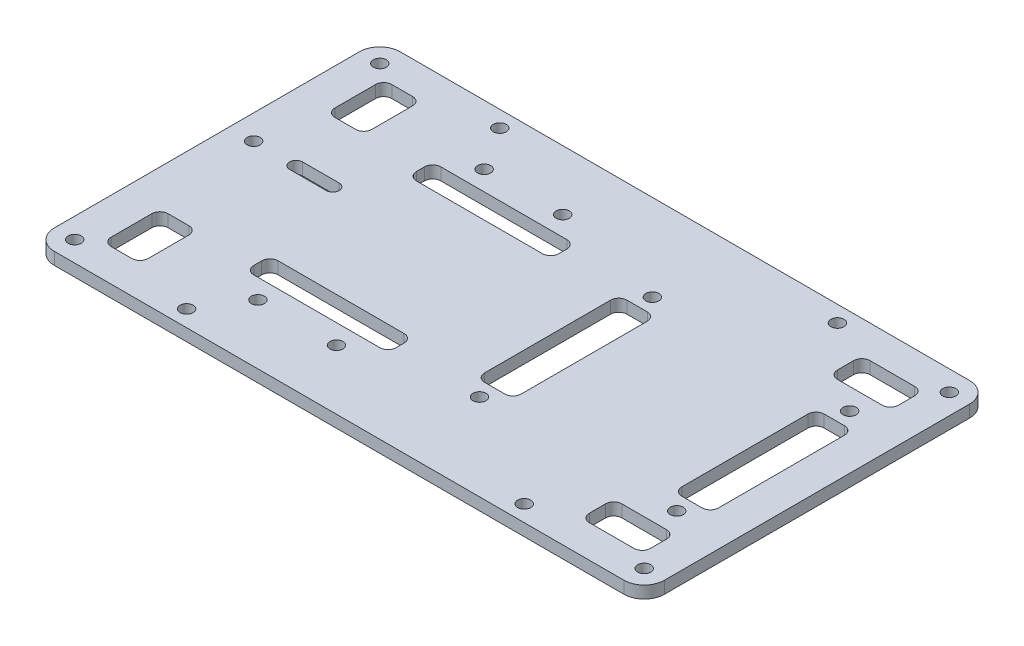
SolidWorks part; units mm, degrees
ref_plane "Front Plane" through (0, 0, 0) normal (0, 0, 1) x (1, 0, 0)
ref_plane "Top Plane" through (0, 0, 0) normal (0, 1, 0) x (1, 0, 0)
ref_plane "Right Plane" through (0, 0, 0) normal (1, 0, 0) x (0, 0, -1)
sketch "Sketch1" plane through (0, 0, 0) normal (0, 1, 0) x (1, 0, 0)
  line L0 (-75, 0) -> (75, 0) construction
  line L1 (-70, 42.5) -> (70, 42.5)
  line L2 (-75, 37.5) -> (-75, -37.5)
  line L3 (-70, -42.5) -> (70, -42.5)
  line L4 (75, 37.5) -> (75, -37.5)
  line L5 (-75, 42.5) -> (75, -42.5) construction
  line L6 (-75, -42.5) -> (75, 42.5) construction
  line L7 (0, 42.5) -> (0, -42.5) construction
  line L8 (37.5, 21.25) -> (37.5, -21.25) construction
  line L9 (13.25, 21.25) -> (61.75, 21.25) construction
  line L10 (13.25, 21.25) -> (13.25, -21.25) construction
  line L11 (13.25, -21.25) -> (61.75, -21.25) construction
  line L12 (61.75, 21.25) -> (61.75, -21.25) construction
  line L13 (13.25, 21.25) -> (61.75, -21.25) construction
  line L14 (13.25, -21.25) -> (61.75, 21.25) construction
  line L15 (10.75, 17.5) -> (15.75, 17.5)
  line L16 (8.75, 15.5) -> (8.75, -15.5)
  line L17 (10.75, -17.5) -> (15.75, -17.5)
  line L18 (17.75, 15.5) -> (17.75, -15.5)
  line L19 (8.75, 17.5) -> (17.75, -17.5) construction
  line L20 (8.75, -17.5) -> (17.75, 17.5) construction
  line L21 (64.25, -17.5) -> (59.25, -17.5)
  line L22 (66.25, 15.5) -> (66.25, -15.5)
  line L23 (64.25, 17.5) -> (59.25, 17.5)
  line L24 (57.25, 15.5) -> (57.25, -15.5)
  line L25 (-25, -27.81) -> (-25, 27.81) construction
  line L26 (-34.65, 27.81) -> (-15.35, 27.81) construction
  line L27 (-34.65, 27.81) -> (-34.65, -27.81) construction
  line L28 (-34.65, -27.81) -> (-15.35, -27.81) construction
  line L29 (-15.35, 27.81) -> (-15.35, -27.81) construction
  line L30 (-34.65, 27.81) -> (-15.35, -27.81) construction
  line L31 (-34.65, -27.81) -> (-15.35, 27.81) construction
  line L32 (-41.5, 38.5) -> (41.5, 38.5) construction
  line L33 (-41.5, 38.5) -> (-41.5, -38.5) construction
  line L34 (-41.5, -38.5) -> (41.5, -38.5) construction
  line L35 (41.5, 38.5) -> (41.5, -38.5) construction
  line L36 (-41.5, 38.5) -> (41.5, -38.5) construction
  line L37 (-41.5, -38.5) -> (41.5, 38.5) construction
  line L38 (-61.5, 8) -> (-61.5, -8) construction
  line L39 (-71.5, 8) -> (-51.5, 8) construction
  line L40 (-71.5, 8) -> (-71.5, -8) construction
  line L41 (-71.5, -8) -> (-51.5, -8) construction
  line L42 (-51.5, 8) -> (-51.5, -8) construction
  line L43 (-71.5, 8) -> (-51.5, -8) construction
  line L44 (-71.5, -8) -> (-51.5, 8) construction
  line L45 (-61.5, 42.5) -> (-61.5, -42.5) construction
  line L46 (-58.54, 7.06) -> (-49.54, 7.06)
  line L47 (-58.54, 7.06) -> (-58.54, 3.86) construction
  line L48 (-58.54, 3.86) -> (-49.54, 3.86)
  line L49 (-49.54, 7.06) -> (-49.54, 3.86) construction
  line L50 (-58.54, 7.06) -> (-49.54, 3.86) construction
  line L51 (-58.54, 3.86) -> (-49.54, 7.06) construction
  line L52 (-64.05, -34.5) -> (-58.95, -34.5)
  line L53 (-64.05, 34.5) -> (-58.95, 34.5)
  line L54 (-66.05, 32.5) -> (-66.05, 22.5)
  line L55 (-64.05, 20.5) -> (-58.95, 20.5)
  line L56 (-56.95, 32.5) -> (-56.95, 22.5)
  line L57 (-66.05, 34.5) -> (-56.95, 20.5) construction
  line L58 (-66.05, 20.5) -> (-56.95, 34.5) construction
  line L59 (-56.95, -32.5) -> (-56.95, -22.5)
  line L60 (-64.05, -20.5) -> (-58.95, -20.5)
  line L61 (-66.05, -32.5) -> (-66.05, -22.5)
  line L62 (53.5201, -34.5) -> (64.4799, -34.5)
  line L63 (53.5201, 34.5) -> (64.4799, 34.5)
  line L64 (51.5, 32.4799) -> (51.5, 28.5201)
  line L65 (53.5201, 26.5) -> (64.4799, 26.5)
  line L66 (66.5, 32.4799) -> (66.5, 28.5201)
  line L67 (51.5, 34.5) -> (66.5, 26.5) construction
  line L68 (51.5, 26.5) -> (66.5, 34.5) construction
  line L69 (51.5, -32.4799) -> (51.5, -28.5201)
  line L70 (53.5201, -26.5) -> (64.4799, -26.5)
  line L71 (66.5, -32.4799) -> (66.5, -28.5201)
  line L72 (-7.5, -20.9799) -> (-7.5, -19.0201)
  line L73 (-40.4799, 23) -> (-9.5201, 23)
  line L74 (-42.5, 20.9799) -> (-42.5, 19.0201)
  line L75 (-40.4799, 17) -> (-9.5201, 17)
  line L76 (-7.5, 20.9799) -> (-7.5, 19.0201)
  line L77 (-42.5, 23) -> (-7.5, 17) construction
  line L78 (-42.5, 17) -> (-7.5, 23) construction
  line L79 (-40.4799, -17) -> (-9.5201, -17)
  line L80 (-42.5, -20.9799) -> (-42.5, -19.0201)
  line L81 (-40.4799, -23) -> (-9.5201, -23)
  circle A0 centre (13.25, 21.25) radius 1.6
  arc A1 (70, 42.5) -> (75, 37.5) centre (70, 37.5) cw
  arc A2 (75, -37.5) -> (70, -42.5) centre (70, -37.5) cw
  arc A3 (-70, -42.5) -> (-75, -37.5) centre (-70, -37.5) cw
  arc A4 (-75, 37.5) -> (-70, 42.5) centre (-70, 37.5) cw
  circle A5 centre (-70, 37.5) radius 1.6
  circle A6 centre (-70, -37.5) radius 1.6
  circle A7 centre (70, -37.5) radius 1.6
  circle A8 centre (70, 37.5) radius 1.6
  circle A9 centre (61.75, 21.25) radius 1.6
  circle A10 centre (13.25, -21.25) radius 1.6
  circle A11 centre (61.75, -21.25) radius 1.6
  arc A12 (15.75, 17.5) -> (17.75, 15.5) centre (15.75, 15.5) cw
  arc A13 (17.75, -15.5) -> (15.75, -17.5) centre (15.75, -15.5) cw
  arc A14 (10.75, -17.5) -> (8.75, -15.5) centre (10.75, -15.5) cw
  arc A15 (8.75, 15.5) -> (10.75, 17.5) centre (10.75, 15.5) cw
  arc A16 (57.25, -15.5) -> (59.25, -17.5) centre (59.25, -15.5) ccw
  arc A17 (64.25, -17.5) -> (66.25, -15.5) centre (64.25, -15.5) ccw
  arc A18 (66.25, 15.5) -> (64.25, 17.5) centre (64.25, 15.5) ccw
  arc A19 (59.25, 17.5) -> (57.25, 15.5) centre (59.25, 15.5) ccw
  circle A20 centre (-34.65, 27.81) radius 1.6
  circle A21 centre (-34.65, -27.81) radius 1.6
  circle A22 centre (-15.35, -27.81) radius 1.6
  circle A23 centre (-15.35, 27.81) radius 1.6
  circle A24 centre (-41.5, 38.5) radius 1.6
  circle A25 centre (-41.5, -38.5) radius 1.6
  circle A26 centre (41.5, -38.5) radius 1.6
  circle A27 centre (41.5, 38.5) radius 1.6
  circle A28 centre (-68.96, 5.46) radius 1.6
  arc A30 (-58.54, 7.06) -> (-58.54, 3.86) centre (-58.54, 5.46) ccw
  arc A31 (-49.54, 3.86) -> (-49.54, 7.06) centre (-49.54, 5.46) ccw
  arc A32 (-58.95, 34.5) -> (-56.95, 32.5) centre (-58.95, 32.5) cw
  arc A33 (-56.95, 22.5) -> (-58.95, 20.5) centre (-58.95, 22.5) cw
  arc A34 (-64.05, 20.5) -> (-66.05, 22.5) centre (-64.05, 22.5) cw
  arc A35 (-66.05, 32.5) -> (-64.05, 34.5) centre (-64.05, 32.5) cw
  arc A36 (-58.95, -34.5) -> (-56.95, -32.5) centre (-58.95, -32.5) ccw
  arc A37 (-56.95, -22.5) -> (-58.95, -20.5) centre (-58.95, -22.5) ccw
  arc A38 (-64.05, -20.5) -> (-66.05, -22.5) centre (-64.05, -22.5) ccw
  arc A39 (-66.05, -32.5) -> (-64.05, -34.5) centre (-64.05, -32.5) ccw
  arc A40 (64.4799, 34.5) -> (66.5, 32.4799) centre (64.4799, 32.4799) cw
  arc A41 (66.5, 28.5201) -> (64.4799, 26.5) centre (64.4799, 28.5201) cw
  arc A42 (53.5201, 26.5) -> (51.5, 28.5201) centre (53.5201, 28.5201) cw
  arc A43 (51.5, 32.4799) -> (53.5201, 34.5) centre (53.5201, 32.4799) cw
  arc A44 (51.5, -32.4799) -> (53.5201, -34.5) centre (53.5201, -32.4799) ccw
  arc A45 (53.5201, -26.5) -> (51.5, -28.5201) centre (53.5201, -28.5201) ccw
  arc A46 (66.5, -28.5201) -> (64.4799, -26.5) centre (64.4799, -28.5201) ccw
  arc A47 (64.4799, -34.5) -> (66.5, -32.4799) centre (64.4799, -32.4799) ccw
  arc A48 (-9.5201, 23) -> (-7.5, 20.9799) centre (-9.5201, 20.9799) cw
  arc A49 (-7.5, 19.0201) -> (-9.5201, 17) centre (-9.5201, 19.0201) cw
  arc A50 (-40.4799, 17) -> (-42.5, 19.0201) centre (-40.4799, 19.0201) cw
  arc A51 (-42.5, 20.9799) -> (-40.4799, 23) centre (-40.4799, 20.9799) cw
  arc A52 (-9.5201, -23) -> (-7.5, -20.9799) centre (-9.5201, -20.9799) ccw
  arc A53 (-7.5, -19.0201) -> (-9.5201, -17) centre (-9.5201, -19.0201) ccw
  arc A54 (-40.4799, -17) -> (-42.5, -19.0201) centre (-40.4799, -19.0201) ccw
  arc A55 (-42.5, -20.9799) -> (-40.4799, -23) centre (-40.4799, -20.9799) ccw
  point P0 (0, 0)
  point P10 (37.5, 0)
  point P35 (13.25, 0)
  point P66 (-25, 0)
  point P71 (0, 0)
  point P86 (-61.5, 0)
  point P95 (-54.04, 5.46)
  point P104 (-61.5, 27.5)
  point P121 (-61.5, 34.5)
  point P122 (-61.5, -34.5)
  point P135 (59, 30.5)
  point P164 (-25, 20)
  dimension "D6" = 3.2
  dimension "D7" = 5
  dimension "D8" = 3.2
  dimension "D9" = 3.2
  dimension "D12" = 2
  dimension "D19" = 3.2
  dimension "D20" = 3.2
  dimension "D24" = 3.2
  dimension "D34" = 2
  dimension "D39" = 2.0201
  dimension "D43" = 2.0201
  dimension "D1" = 150
  dimension "D2" = 85
  dimension "D3" = 48.5
  dimension "D4" = 42.5
  dimension "D5" = 37.5
  dimension "D10" = 35
  dimension "D11" = 9
  dimension "D13" = 24.25
  dimension "D14" = 50
  dimension "D15" = 19.3
  dimension "D16" = 55.62
  dimension "D17" = 83
  dimension "D18" = 77
  dimension "D21" = 16
  dimension "D22" = 20
  dimension "D23" = 20
  dimension "D25" = 2.54
  dimension "D26" = 2.54
  dimension "D27" = 2.54
  dimension "D28" = 2.54
  dimension "D29" = 3.2
  dimension "D30" = 9
  dimension "D31" = 14
  dimension "D32" = 9.1
  dimension "D33" = 15
  dimension "D35" = 12
  dimension "D36" = 16
  dimension "D37" = 8
  dimension "D38" = 15
  dimension "D40" = 35
  dimension "D41" = 6
  dimension "D42" = 20
extrude "Boss-Extrude1" add sketch "Sketch1" along normal blind 3
